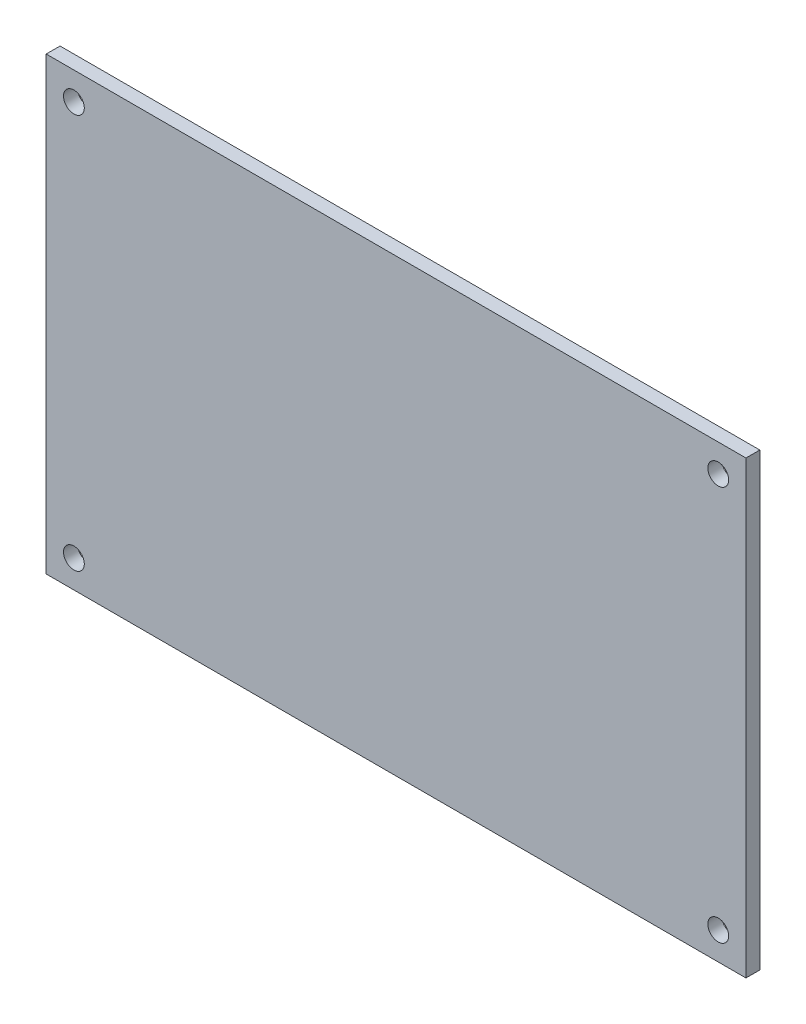
SolidWorks part; units mm, degrees
ref_plane "Ön Düzlem" through (0, 0, 0) normal (0, 0, 1) x (1, 0, 0)
ref_plane "Üst Düzlem" through (0, 0, 0) normal (0, 1, 0) x (1, 0, 0)
ref_plane "Sağ Düzlem" through (0, 0, 0) normal (1, 0, 0) x (0, 0, -1)
sketch "Çizim1" plane through (0, 0, 0) normal (0, 0, 1) x (1, 0, 0)
  line L1 (0, 0) -> (101, 0)
  line L2 (0, 0) -> (0, 65)
  line L3 (0, 65) -> (101, 65)
  line L4 (101, 0) -> (101, 65)
  dimension "D1" = 101
  dimension "D2" = 65
extrude "Yükseklik-Ekstrüzyon1" add sketch "Çizim1" along normal blind 2
sketch "Sketch1" plane through (0, 0, 2) normal (0, 0, 1) x (1, 0, 0)
  line L0 (101, 65) -> (0, 65) construction
  line L1 (0, 65) -> (0, 0) construction
  line L2 (101, 0) -> (101, 65) construction
  line L3 (0, 0) -> (101, 0) construction
  circle A0 centre (4, 61) radius 1.5
  circle A1 centre (97, 61) radius 1.5
  circle A2 centre (97, 4) radius 1.5
  circle A3 centre (4, 4) radius 1.5
  dimension "D1" = 4
  dimension "D3" = 4
  dimension "D4" = 4
  dimension "D2" = 4
extrude "Cut-Extrude1" cut sketch "Sketch1" against normal through all
